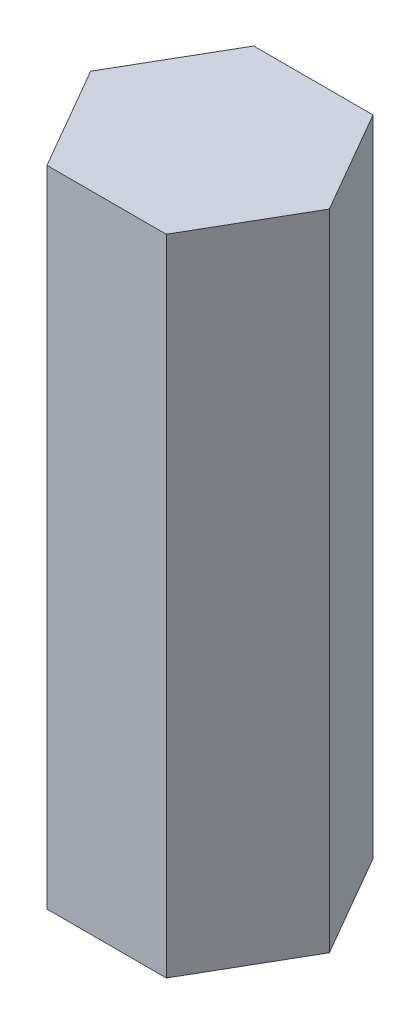
SolidWorks part; units mm, degrees
ref_plane "Front Plane" through (0, 0, 0) normal (0, 0, 1) x (1, 0, 0)
ref_plane "Top Plane" through (0, 0, 0) normal (0, 1, 0) x (1, 0, 0)
ref_plane "Right Plane" through (0, 0, 0) normal (1, 0, 0) x (0, 0, -1)
sketch "Sketch1" plane through (0, 0, 0) normal (0, 1, 0) x (1, 0, 0)
  line L1 (3, 0) -> (1.5, 2.5981)
  line L2 (1.5, 2.5981) -> (-1.5, 2.5981)
  line L3 (-1.5, 2.5981) -> (-3, 0)
  line L4 (-3, 0) -> (-1.5, -2.5981)
  line L5 (-1.5, -2.5981) -> (1.5, -2.5981)
  line L6 (1.5, -2.5981) -> (3, 0)
  circle A0 centre (0, 0) radius 2.5981 construction
  dimension "D1" = 3
extrude "Boss-Extrude1" add sketch "Sketch1" along normal blind 16.19
sketch "Sketch3" plane through (0, 0, 0) normal (0, -1, 0) x (1, 0, 0)
  circle A0 centre (0, 0) radius 1.6
  dimension "D1" = 3.2
extrude "Cut-Extrude1" cut sketch "Sketch3" against normal blind 5
